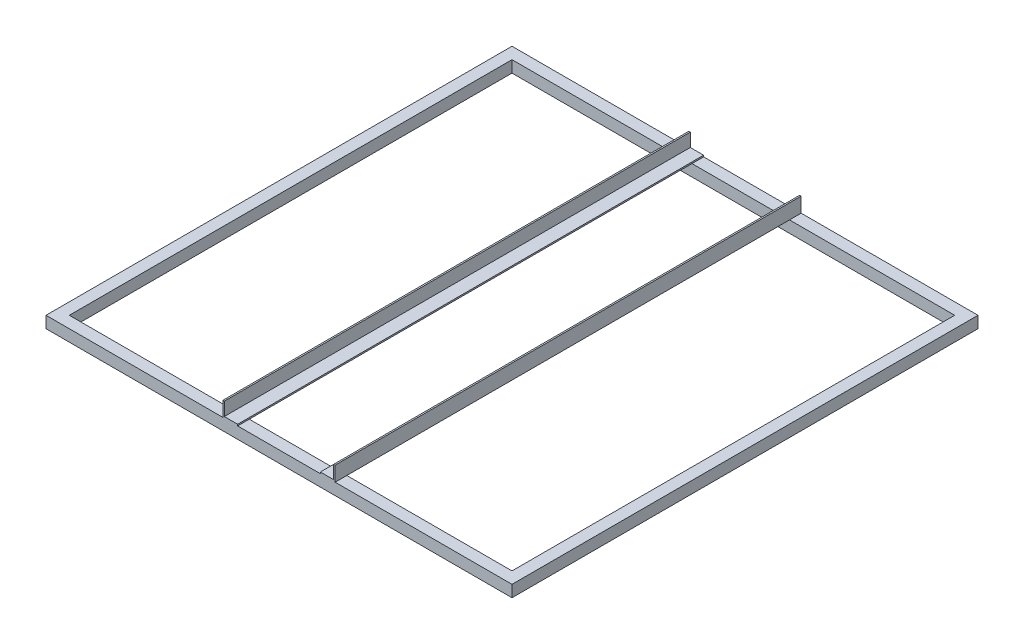
SolidWorks part; units mm, degrees
ref_plane "Front Plane" through (0, 0, 0) normal (0, 0, 1) x (1, 0, 0)
ref_plane "Top Plane" through (0, 0, 0) normal (0, 1, 0) x (1, 0, 0)
ref_plane "Right Plane" through (0, 0, 0) normal (1, 0, 0) x (0, 0, -1)
sketch "Sketch1" plane through (0, 0, 0) normal (0, 1, 0) x (1, 0, 0)
  line L1 (-400, 400) -> (400, 400)
  line L2 (-400, 400) -> (-400, -400)
  line L3 (-400, -400) -> (400, -400)
  line L4 (400, 400) -> (400, -400)
  line L5 (-400, 400) -> (400, -400) construction
  line L6 (-400, -400) -> (400, 400) construction
  line L7 (380, 380) -> (-380, 380)
  line L8 (380, 380) -> (380, -380)
  line L9 (380, -380) -> (-380, -380)
  line L10 (-380, 380) -> (-380, -380)
  line L11 (380, 380) -> (-380, -380) construction
  line L12 (380, -380) -> (-380, 380) construction
  point P0 (0, 0)
  point P6 (0, 0)
  dimension "D1" = 800
  dimension "D2" = 800
  dimension "D3" = 760
extrude "Boss-Extrude1" add sketch "Sketch1" along normal blind 20
sketch "Sketch2" plane through (0, 20, 0) normal (0, 1, 0) x (1, 0, 0)
  line L0 (0, 400) -> (0, -400) construction
  line L3 (400, 400) -> (-400, 400) construction
  line L4 (-400, -400) -> (400, -400) construction
  line L5 (0, -400) -> (71, -400) construction
  line L6 (0, -400) -> (-71, -400) construction
  line L8 (71, -400) -> (96.4, -400)
  line L9 (71, -400) -> (71, 400)
  line L10 (71, 400) -> (96.4, 400)
  line L11 (96.4, -400) -> (96.4, 400)
  line L12 (-71, -400) -> (-96.4, -400)
  line L13 (-71, -400) -> (-71, 400)
  line L14 (-71, 400) -> (-96.4, 400)
  line L15 (-96.4, -400) -> (-96.4, 400)
  dimension "D1" = 71
  dimension "D2" = 71
  dimension "D3" = 25.4
extrude "Boss-Extrude2" add sketch "Sketch2" along normal blind 2.5
sketch "Sketch3" plane through (0, 22.5, 0) normal (0, 1, 0) x (1, 0, 0)
  line L0 (-96.4, -400) -> (-71, -400) construction
  line L1 (-96.4, 400) -> (-93.9, 400)
  line L2 (-96.4, 400) -> (-96.4, -400)
  line L3 (-96.4, -400) -> (-93.9, -400)
  line L4 (-93.9, 400) -> (-93.9, -400)
  line L5 (96.4, 400) -> (71, 400) construction
  line L6 (96.4, -400) -> (93.9, -400)
  line L7 (96.4, -400) -> (96.4, 400)
  line L8 (96.4, 400) -> (93.9, 400)
  line L9 (93.9, -400) -> (93.9, 400)
  dimension "D1" = 2.5
extrude "Boss-Extrude3" add sketch "Sketch3" along normal blind 22.9
